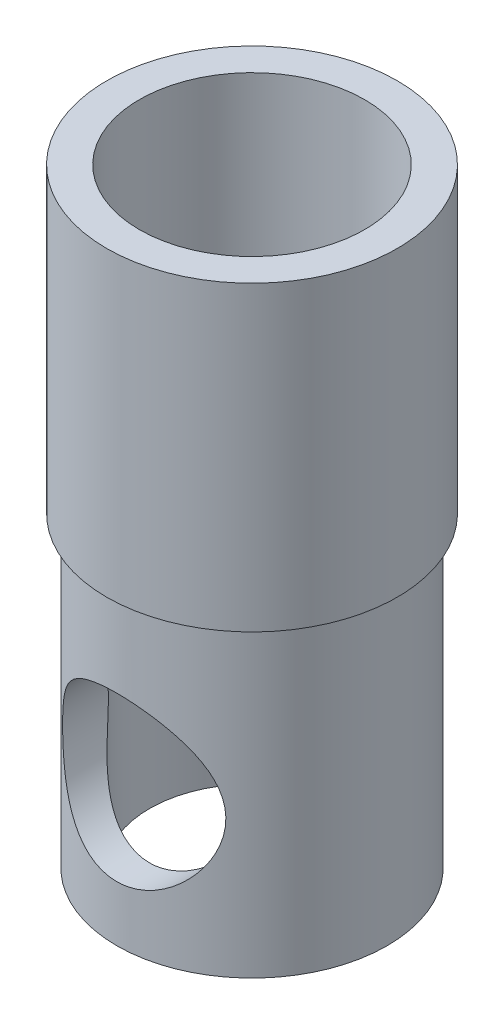
SolidWorks part; units mm, degrees
material "PTFE (general)"
ref_plane "Front Plane" through (0, 0, 0) normal (0, 0, 1) x (1, 0, 0)
ref_plane "Top Plane" through (0, 0, 0) normal (0, 1, 0) x (1, 0, 0)
ref_plane "Right Plane" through (0, 0, 0) normal (1, 0, 0) x (0, 0, -1)
sketch "Sketch1" plane through (0, 0, 0) normal (0, 1, 0) x (1, 0, 0)
  circle A0 centre (0, 0) radius 8.28
  circle A1 centre (0, 0) radius 6.28
  dimension "D1" = 16.56
  dimension "D2" = 12.56
extrude "Boss-Extrude1" add sketch "Sketch1" along normal blind 1 and the other way blind 17.8
sketch "Sketch2" plane through (0, 1, 0) normal (0, 1, 0) x (1, 0, 0)
  circle A0 centre (0, 0) radius 8.9
  circle A1 centre (0, 0) radius 6.9
  dimension "D1" = 17.8
  dimension "D2" = 13.8
extrude "Boss-Extrude2" add sketch "Sketch2" along normal blind 18.5
sketch "Sketch3" plane through (0, 0, 0) normal (0, 0, 1) x (1, 0, 0)
  line L0 (-8.28, -17.8) -> (8.28, -17.8) construction
  circle A0 centre (0, -9.4) radius 5
  dimension "D1" = 10
  dimension "D2" = 8.4
extrude "Cut-Extrude1" cut sketch "Sketch3" along normal through all
